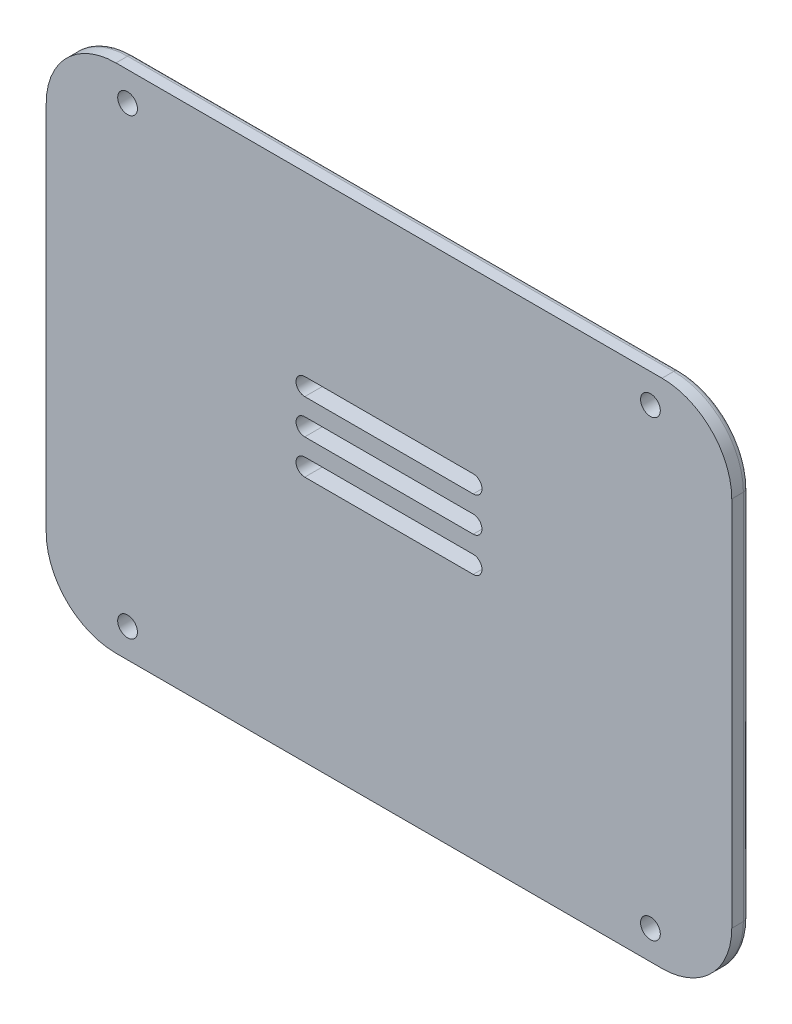
SolidWorks part; units mm, degrees
ref_plane "Front Plane" through (0, 0, 0) normal (0, 0, 1) x (1, 0, 0)
ref_plane "Top Plane" through (0, 0, 0) normal (0, 1, 0) x (1, 0, 0)
ref_plane "Right Plane" through (0, 0, 0) normal (1, 0, 0) x (0, 0, -1)
sketch "Sketch1" plane through (0, 0, 0) normal (0, 0, 1) x (1, 0, 0)
  line L1 (-47, -44) -> (47, -44)
  line L2 (-59, -32) -> (-59, 32)
  line L3 (-47, 44) -> (47, 44)
  line L4 (59, -32) -> (59, 32)
  line L5 (-59, -44) -> (59, 44) construction
  line L6 (-59, 44) -> (59, -44) construction
  arc A0 (47, 44) -> (59, 32) centre (47, 32) cw
  arc A1 (47, -44) -> (59, -32) centre (47, -32) ccw
  arc A2 (-47, -44) -> (-59, -32) centre (-47, -32) cw
  arc A3 (-59, 32) -> (-47, 44) centre (-47, 32) cw
  point P0 (0, 0)
  dimension "D3" = 12
  dimension "D1" = 118
  dimension "D2" = 88
extrude "Boss-Extrude1" add sketch "Sketch1" along normal blind 3
fillet "Fillet1" radius 1 8 edges at (59, 0, 0) (0, -44, 0) (-59, 0, 0) (0, 44, 0) (-55.4853, 40.4853, 0) (-55.4853, -40.4853, 0) (55.4853, -40.4853, 0) (55.4853, 40.4853, 0)
sketch "Sketch2" plane through (0, 0, 0) normal (0, 0, -1) x (-1, 0, 0)
  circle A0 centre (-45, 39) radius 1.7
  circle A1 centre (-45, -39) radius 1.7
  circle A2 centre (45, -39) radius 1.7
  circle A3 centre (45, 39) radius 1.7
  point P8 (0, 0)
  point P9 (0, 0)
  dimension "D1" = 3.4
  dimension "D2" = 3.4
  dimension "D3" = 3.4
  dimension "D4" = 3.4
  dimension "D5" = 39
  dimension "D6" = 45
  dimension "D7" = 39
  dimension "D8" = 45
  dimension "D9" = 45
  dimension "D10" = 39
  dimension "D11" = 39
  dimension "D12" = 45
extrude "Cut-Extrude2" cut sketch "Sketch2" against normal through all contours A0 | A3 | A1 | A2
sketch "Sketch6" plane through (0, 0, 0) normal (0, 0, -1) x (-1, 0, 0)
  line L0 (-14.5, 0) -> (14.5, 0) construction
  line L1 (-14.5, 1.5) -> (14.5, 1.5)
  line L2 (-14.5, -1.5) -> (14.5, -1.5)
  line L3 (-14.5, 6) -> (14.5, 6) construction
  line L4 (-14.5, 7.5) -> (14.5, 7.5)
  line L5 (-14.5, 4.5) -> (14.5, 4.5)
  line L6 (-14.5, 12) -> (14.5, 12) construction
  line L7 (-14.5, 13.5) -> (14.5, 13.5)
  line L8 (-14.5, 10.5) -> (14.5, 10.5)
  arc A0 (-14.5, 1.5) -> (-14.5, -1.5) centre (-14.5, 0) ccw
  arc A1 (14.5, -1.5) -> (14.5, 1.5) centre (14.5, 0) ccw
  arc A2 (-14.5, 7.5) -> (-14.5, 4.5) centre (-14.5, 6) ccw
  arc A3 (14.5, 4.5) -> (14.5, 7.5) centre (14.5, 6) ccw
  arc A4 (-14.5, 13.5) -> (-14.5, 10.5) centre (-14.5, 12) ccw
  arc A5 (14.5, 10.5) -> (14.5, 13.5) centre (14.5, 12) ccw
  point P2 (0, 0)
  point P8 (0, 0)
  point P9 (0, 0)
  point P12 (0, 6)
  point P19 (0, 12)
  point P24 (0, 0)
  dimension "D1" = 1.5
  dimension "D2" = 29
  dimension "D3" = 3
extrude "Cut-Extrude3" cut sketch "Sketch6" against normal through all
